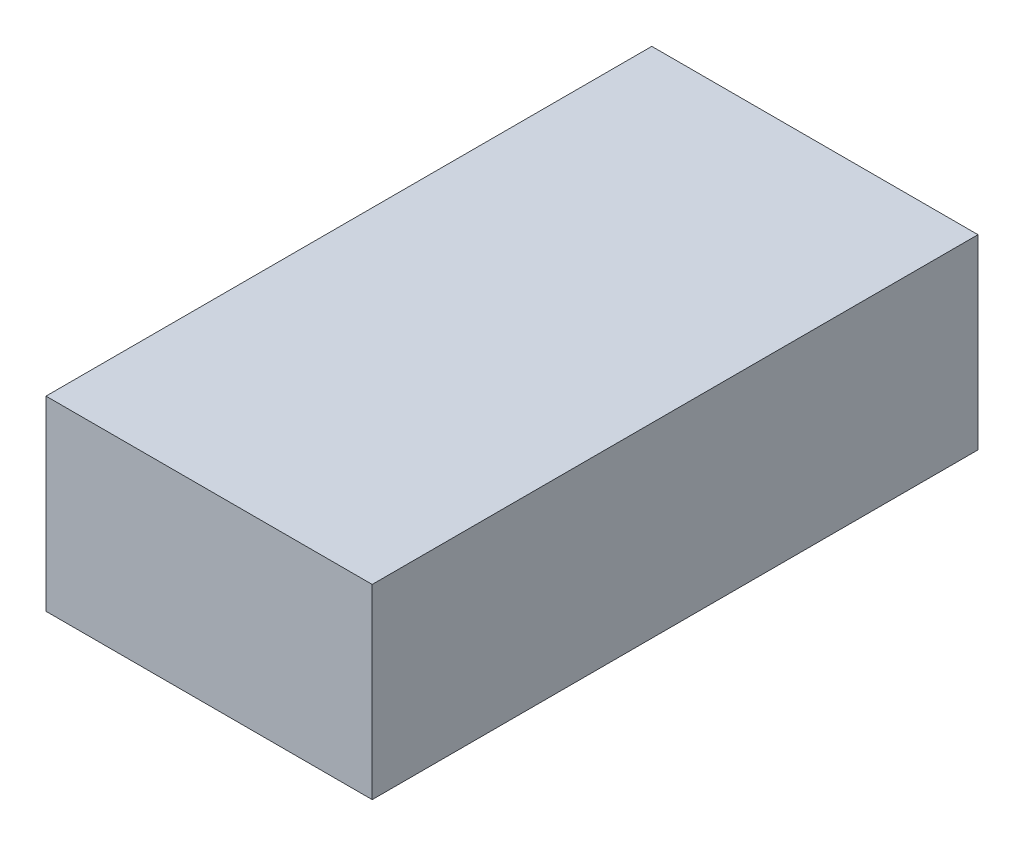
SolidWorks part; units mm, degrees
ref_plane "Front Plane" through (0, 0, 0) normal (0, 0, 1) x (1, 0, 0)
ref_plane "Top Plane" through (0, 0, 0) normal (0, 1, 0) x (1, 0, 0)
ref_plane "Right Plane" through (0, 0, 0) normal (1, 0, 0) x (0, 0, -1)
other "Configuration Table"
sketch "Sketch1" plane through (0, 0, 0) normal (0, 0, 1) x (1, 0, 0)
  line L1 (60, 1174) -> (200, 1174)
  line L2 (60, 1174) -> (60, 1254)
  line L3 (60, 1254) -> (200, 1254)
  line L4 (200, 1174) -> (200, 1254)
extrude "PRESS_uc_pence_govde_1" add sketch "Sketch1" against normal blind 260 from offset 100 separate body
